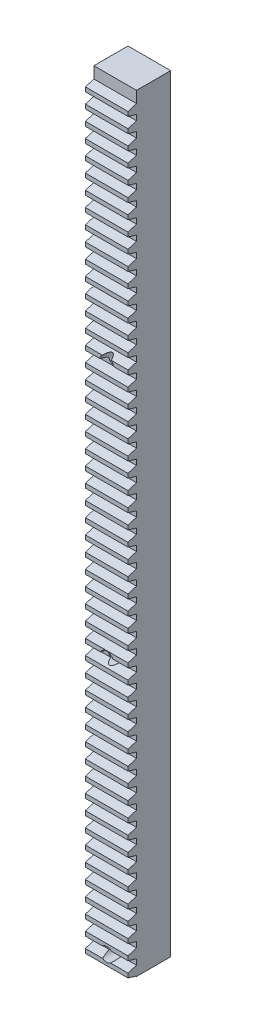
SolidWorks part; units mm, degrees
ref_plane "前视基准面" through (0, 0, 0) normal (0, 0, 1) x (1, 0, 0)
ref_plane "上视基准面" through (0, 0, 0) normal (0, 1, 0) x (1, 0, 0)
ref_plane "右视基准面" through (0, 0, 0) normal (1, 0, 0) x (0, 0, -1)
sketch "草图1" plane through (0, 0, 0) normal (1, 0, 0) x (0, 0, -1)
  line L1 (0, 90) -> (8, 90)
  line L2 (0, 90) -> (0, -90)
  line L3 (0, -90) -> (8, -90)
  line L4 (8, 90) -> (8, -90)
  dimension "D1" = 8
  dimension "D2" = 180
extrude "凸台-拉伸1" add sketch "草图1" along normal mid plane 10
sketch "草图2" plane through (0, 0, 0) normal (1, 0, 0) x (0, 0, -1)
  line L0 (0, -89.9) -> (-2, -89.3)
  line L1 (0, 90) -> (0, -90) construction
  line L2 (-2, -89.3) -> (-2, -88.3)
  line L3 (-2, -88.3) -> (0, -87.7)
  line L4 (-2, -88.8) -> (0.7599, -88.8) construction
  line L5 (0, -89.9) -> (0, -87.7)
  line L6 (0, -90) -> (8, -90) construction
  dimension "D1" = 1
  dimension "D2" = 2
  dimension "D3" = 2.2
  dimension "D4" = 1.2
extrude "凸台-拉伸2" add sketch "草图2" along normal mid plane 10
pattern_linear "阵列(线性)1" count 51 spacing 3.5 along (0, 1, 0) of "凸台-拉伸2"
sketch "草图3" plane through (0, 0, -8) normal (0, 0, -1) x (-1, 0, 0)
  line L0 (0, -90) -> (0, 90) construction
  line L1 (-5, -90) -> (5, -90) construction
  line L2 (-5, 90) -> (5, 90) construction
  line L3 (0, -27) -> (65.8116, -27) construction
  line L4 (-5, -90) -> (5, -90) construction
  circle A0 centre (0, -87) radius 1.6
  circle A1 centre (0, -27) radius 1.6
  circle A2 centre (0, 33) radius 1.6
  dimension "D1" = 120
  dimension "D2" = 3.2
  dimension "D3" = 3
extrude "切除-拉伸1" cut sketch "草图3" against normal through all
